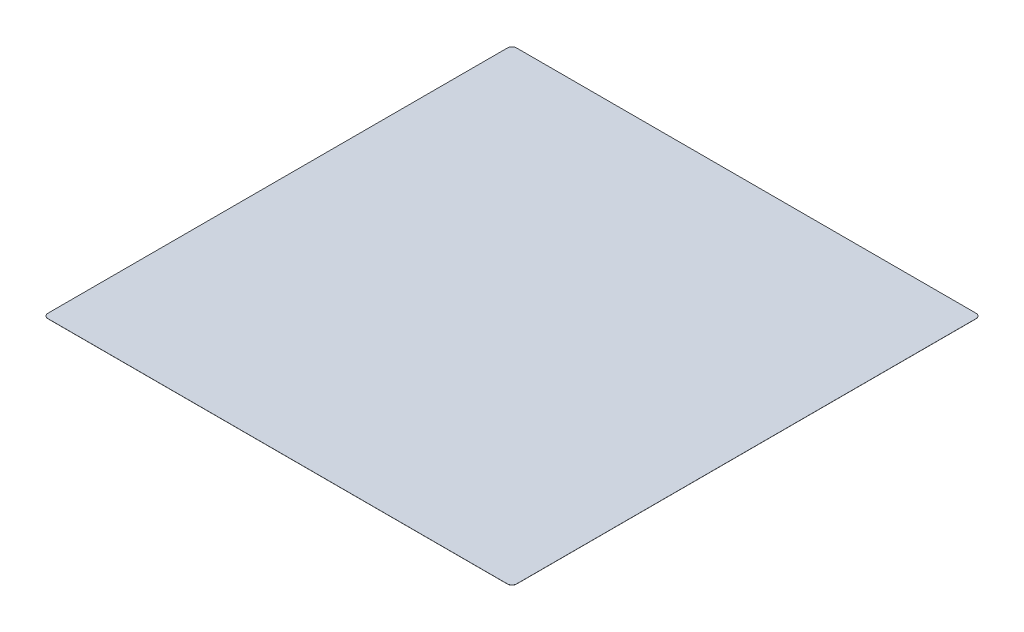
SolidWorks part; units mm, degrees
ref_plane "Front Plane" through (0, 0, 0) normal (0, 0, 1) x (1, 0, 0)
ref_plane "Top Plane" through (0, 0, 0) normal (0, 1, 0) x (1, 0, 0)
ref_plane "Right Plane" through (0, 0, 0) normal (1, 0, 0) x (0, 0, -1)
sketch "Sketch1" plane through (0, 0, 0) normal (0, 1, 0) x (1, 0, 0)
  line L5 (-50, 50) -> (50, 50)
  line L6 (-50, 50) -> (-50, -50)
  line L7 (-50, -50) -> (50, -50)
  line L8 (50, 50) -> (50, -50)
  line L9 (-50, 50) -> (50, -50) construction
  line L10 (-50, -50) -> (50, 50) construction
  point P0 (0, 0)
  dimension "D1" = 100
extrude "Boss-Extrude1" add sketch "Sketch1" along normal mid plane 0.0254
fillet "Fillet1" radius 1 4 edges at (50, 0, 50) (-50, 0, 50) (-50, 0, -50) (50, 0, -50)
